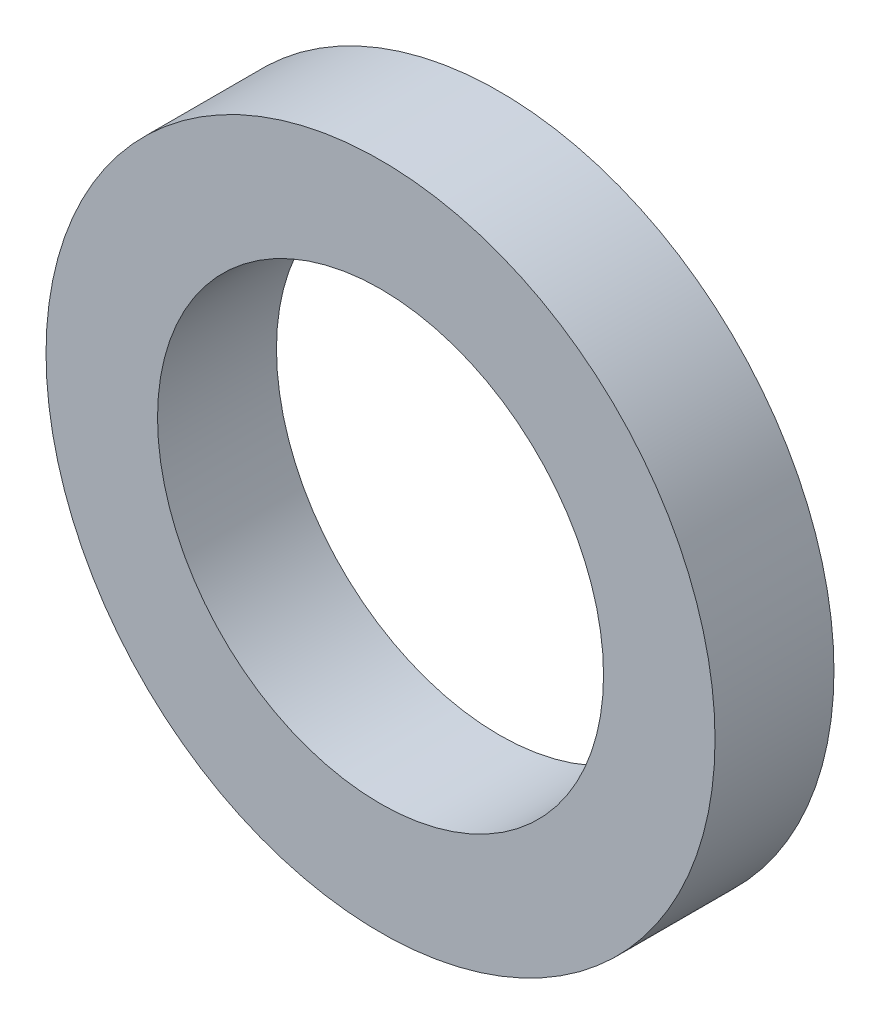
SolidWorks part; units mm, degrees
ref_plane "Top Plane" through (0, 0, 0) normal (0, 0, 1) x (1, 0, 0)
ref_plane "Right Plane" through (0, 0, 0) normal (0, 1, 0) x (1, 0, 0)
ref_plane "Front Plane" through (0, 0, 0) normal (1, 0, 0) x (0, 0, -1)
sketch "Sketch1" plane through (0, 0, 0) normal (0, 0, 1) x (1, 0, 0)
  circle A0 centre (0, 0) radius 15
  circle A1 centre (0, 0) radius 22.5
  dimension "D1" = 45
  dimension "D2" = 30
extrude "Boss-Extrude1" add sketch "Sketch1" along normal blind 8
